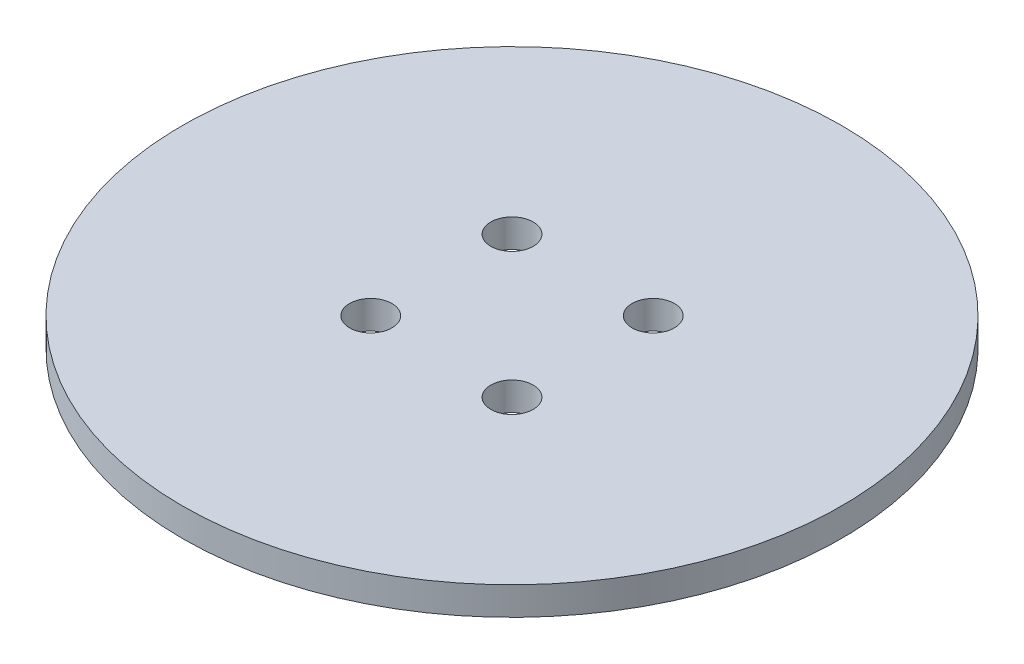
SolidWorks part; units mm, degrees
material "Oak"
ref_plane "Front Plane" through (0, 0, 0) normal (0, 0, 1) x (1, 0, 0)
ref_plane "Top Plane" through (0, 0, 0) normal (0, 1, 0) x (1, 0, 0)
ref_plane "Right Plane" through (0, 0, 0) normal (1, 0, 0) x (0, 0, -1)
sketch "Sketch1" plane through (0, 0, 0) normal (0, 1, 0) x (1, 0, 0)
  circle A0 centre (0, 0) radius 35
  dimension "D1" = 70
extrude "Boss-Extrude1" add sketch "Sketch1" along normal blind 3
sketch "Sketch3" [suppressed] plane through (0, 3, 0) normal (0, 1, 0) x (1, 0, 0)
  line L0 (0, 0) -> (0, -10)
  line L1 (0, 0) -> (8.6603, 5)
  line L2 (0, 0) -> (-8.6603, 5)
  circle A3 centre (-8.6603, 5) radius 1.5
  circle A4 centre (8.6603, 5) radius 1.5
  circle A5 centre (0, -10) radius 1.5
  dimension "D6" = 3
  dimension "D7" = 3
  dimension "D8" = 3
  dimension "D1" = 10
  dimension "D2" = 10
  dimension "D3" = 10
  dimension "D4" = 120
  dimension "D5" = 120
extrude "Cut-Extrude2" [suppressed] cut sketch "Sketch3" against normal through all contours A5 | A4 | A3
hole_wizard "#8 Clearance Hole1" positions "Sketch4" profile "Sketch5" hole size "#8" standard "ANSI Inch" end condition through all
sketch "Sketch4" plane through (0, 3, 0) normal (0, 1, 0) x (1, 0, 0)
  point P0 (-7.5, 7.5)
  point P2 (7.5, 7.5)
  point P4 (-7.5, -7.5)
  point P6 (7.5, -7.5)
  dimension "D1" = 15
  dimension "D2" = 15
  dimension "D3" = 7.5
  dimension "D4" = 7.5
sketch "Sketch5" plane through (-7.5, 3, -7.5) normal (1, 0, 0) x (0, 0, 1)
  line L0 (0, 0) -> (0, 3)
  line L1 (0, 3) -> (2.2479, 3)
  line L2 (2.2479, 3) -> (2.2479, 0)
  line L5 (2.2479, 0) -> (0, 0)
  line L11 (0, -6.35) -> (0, 107.95) construction
  dimension "Thru Hole Dia." = 4.4958
  dimension "Thru Hole Depth" = 3
equation "\"D3@Sketch4\"=\"D1@Sketch4\"/2"
equation "\"D4@Sketch4\"=\"D2@Sketch4\"/2"
